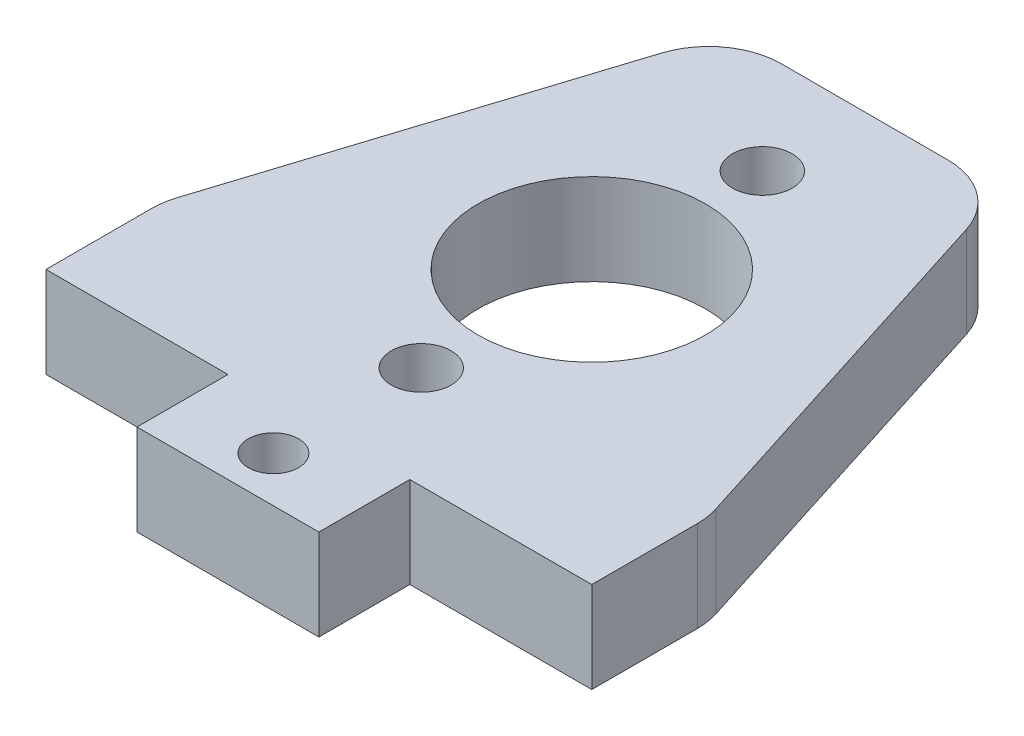
SolidWorks part; units mm, degrees
ref_plane "Front Plane" through (0, 0, 0) normal (0, 0, 1) x (1, 0, 0)
ref_plane "Top Plane" through (0, 0, 0) normal (0, 1, 0) x (1, 0, 0)
ref_plane "Right Plane" through (0, 0, 0) normal (1, 0, 0) x (0, 0, -1)
sketch "Sketch1" plane through (0, 0, 0) normal (0, 1, 0) x (1, 0, 0)
  line L0 (-19.05, -38.1) -> (-6.35, -38.1)
  line L1 (-19.05, -38.1) -> (-19.05, -29.9466)
  line L2 (19.05, -38.1) -> (19.05, -29.9466)
  line L3 (-6.35, -38.1) -> (-6.35, -44.45)
  line L4 (-6.35, -44.45) -> (6.35, -44.45)
  line L5 (6.35, -44.45) -> (6.35, -38.1)
  line L6 (6.35, -38.1) -> (19.05, -38.1)
  line L7 (-15.2978, 0) -> (18.8785, 0) construction
  line L8 (-9.525, 0) -> (9.525, 0)
  line L9 (-9.525, 0) -> (-19.05, -29.9466)
  line L10 (9.525, 0) -> (19.05, -29.9466)
  line L11 (0, 0) -> (0, -44.45) construction
  line L12 (-6.35, -41.275) -> (0, -41.275) construction
  line L13 (0, -21.0141) -> (0, -8.3141) construction
  line L14 (0, -21.0141) -> (0, -33.7141) construction
  circle A0 centre (0, -41.275) radius 1.7526
  dimension "D7" = 3.5052
  dimension "D1" = 38.1
  dimension "D2" = 8.1534
  dimension "D3" = 6.35
  dimension "D4" = 12.7
  dimension "D5" = 44.45
  dimension "D6" = 19.05
extrude "Boss-Extrude1" add sketch "Sketch1" along normal mid plane 6.35
fillet "Fillet1" radius 5.08 2 edges at (9.525, 0, 0) (-9.525, 0, 0)
fillet "Fillet2" radius 5.08 2 edges at (-19.05, 0, 29.9466) (19.05, 0, 29.9466)
sketch "Sketch2" plane through (0, 3.175, 0) normal (0, 1, 0) x (1, 0, 0)
  line L0 (-20.0557, -19.05) -> (20.0557, -19.05) construction
  line L1 (0, -44.45) -> (0, 0) construction
  line L2 (-6.35, -44.45) -> (6.35, -44.45) construction
  line L3 (5.81, 0) -> (-5.81, 0) construction
  line L4 (0, -7.1437) -> (0, -30.9562) construction
  circle A1 centre (0, -7.1437) radius 2.0828
  circle A3 centre (0, -19.05) radius 7.9375
  circle A4 centre (0, -30.9562) radius 2.0828
  point P8 (0, -19.05)
  dimension "D2" = 4.1656
  dimension "D3" = 15.875
  dimension "D1" = 23.8125
  dimension "D4" = 25.4
extrude "Cut-Extrude1" cut sketch "Sketch2" against normal through all
